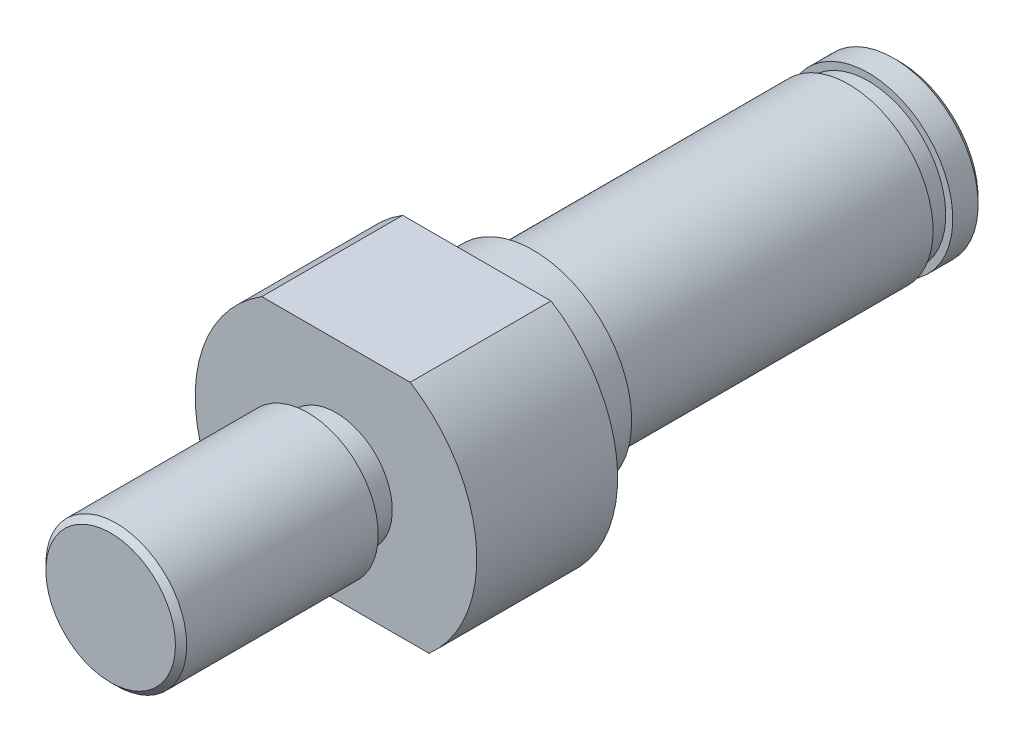
SolidWorks part; units mm, degrees
ref_plane "前视基准面" through (0, 0, 0) normal (0, 0, 1) x (1, 0, 0)
ref_plane "上视基准面" through (0, 0, 0) normal (0, 1, 0) x (1, 0, 0)
ref_plane "右视基准面" through (0, 0, 0) normal (1, 0, 0) x (0, 0, -1)
sketch "草图1" plane through (0, 0, 0) normal (0, 0, 1) x (1, 0, 0)
  line L1 (-2.6339, 4.25) -> (2.6339, 4.25)
  line L3 (-3.3072, -3.75) -> (3.3072, -3.75)
  arc A0 (-2.6339, 4.25) -> (-3.3072, -3.75) centre (0, 0) ccw
  arc A1 (3.3072, -3.75) -> (2.6339, 4.25) centre (0, 0) ccw
  dimension "D1" = 10
  dimension "D2" = 8
extrude "拉伸1" add sketch "草图1" along normal blind 5
sketch "草图2" plane through (0, 0, 5) normal (0, 0, 1) x (1, 0, 0)
  circle A0 centre (0, 0) radius 2.5
  dimension "D1" = 5
extrude "拉伸2" add sketch "草图2" along normal blind 8
cosmetic thread "装饰螺纹线1" parameters "D1"=7, "D2"=5.2
sketch "草图3" plane through (0, 0, 0) normal (0, 0, -1) x (-1, 0, 0)
  circle A0 centre (0, 0) radius 3
  dimension "D1" = 6
extrude "拉伸3" add sketch "草图3" along normal blind 15
sketch "草图5" plane through (0, 0, 0) normal (0, 0, -1) x (-1, 0, 0)
  circle A0 centre (0, 0) radius 3.5
  dimension "D1" = 7
extrude "拉伸4" add sketch "草图5" along normal blind 2
sketch "草图4" plane through (0, 0, 0) normal (0, 1, 0) x (1, 0, 0)
  line L0 (-3, 15) -> (-3, 2) construction
  line L1 (-3, 13.9) -> (-2.75, 13.9)
  line L2 (-3, 13.9) -> (-3, 13.2)
  line L3 (-3, 13.2) -> (-2.75, 13.2)
  line L4 (-2.75, 13.9) -> (-2.75, 13.2)
  line L6 (-5, -5) -> (-2.6339, -5) construction
  line L7 (-3.324, -5) -> (-2, -5)
  line L8 (-3.324, -5) -> (-3.324, -6)
  line L9 (-3.324, -6) -> (-2, -6)
  line L10 (-2, -5) -> (-2, -6)
  line L11 (-3.324, -5) -> (-2, -6) construction
  line L12 (-3.324, -6) -> (-2, -5) construction
  line L13 (-2.5, -5) -> (-2.5, -13) construction
  line L14 (3.5, 2) -> (-3.5, 2) construction
  point P8 (-2.662, -5.5)
  dimension "D1" = 11.2
  dimension "D2" = 0.7
  dimension "D3" = 0.25
  dimension "D4" = 1
  dimension "D5" = 0.5
revolve "切除-旋转1" cut sketch "草图4" angle 360 about axis through (0, 0, -15) along (0, 0, 1)
chamfer "倒角1" distance 0.2 angle 45 2 edges at (2.5, 0, 13) (-3, 0, -15)
